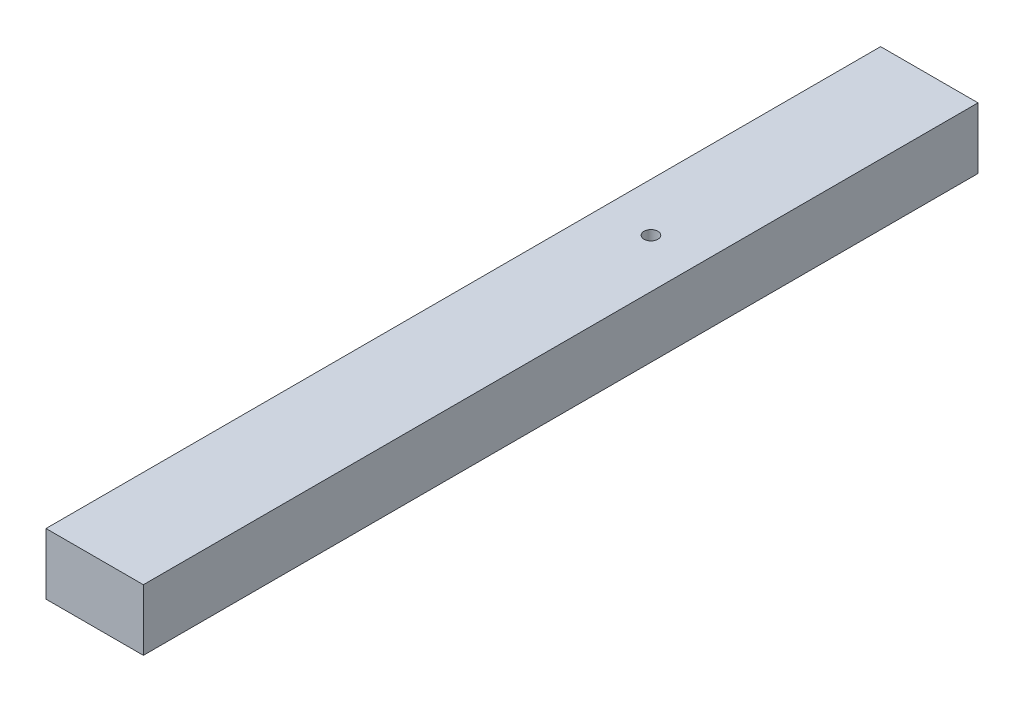
SolidWorks part; units mm, degrees
ref_plane "Front Plane" through (0, 0, 0) normal (0, 0, 1) x (1, 0, 0)
ref_plane "Top Plane" through (0, 0, 0) normal (0, 1, 0) x (1, 0, 0)
ref_plane "Right Plane" through (0, 0, 0) normal (1, 0, 0) x (0, 0, -1)
sketch "Sketch2" plane through (0, 0, 0) normal (0, 0, 1) x (1, 0, 0)
  line L1 (0, 0) -> (70, 0)
  line L2 (0, 0) -> (0, 44)
  line L3 (0, 44) -> (70, 44)
  line L4 (70, 0) -> (70, 44)
  dimension "D1" = 70
  dimension "D2" = 44
extrude "Extrude1" add sketch "Sketch2" along normal blind 600
sketch "Sketch3" plane through (0, 44, 0) normal (0, 1, 0) x (-1, 0, 0)
  line L0 (-34.838, 0) -> (-35, 600) construction
  line L1 (-70, 0) -> (0, 0) construction
  line L2 (-70, 600) -> (0, 600) construction
  circle A0 centre (-34.892, 200) radius 5
  dimension "D1" = 200
extrude "Cut-Extrude1" cut sketch "Sketch3" against normal up to next
